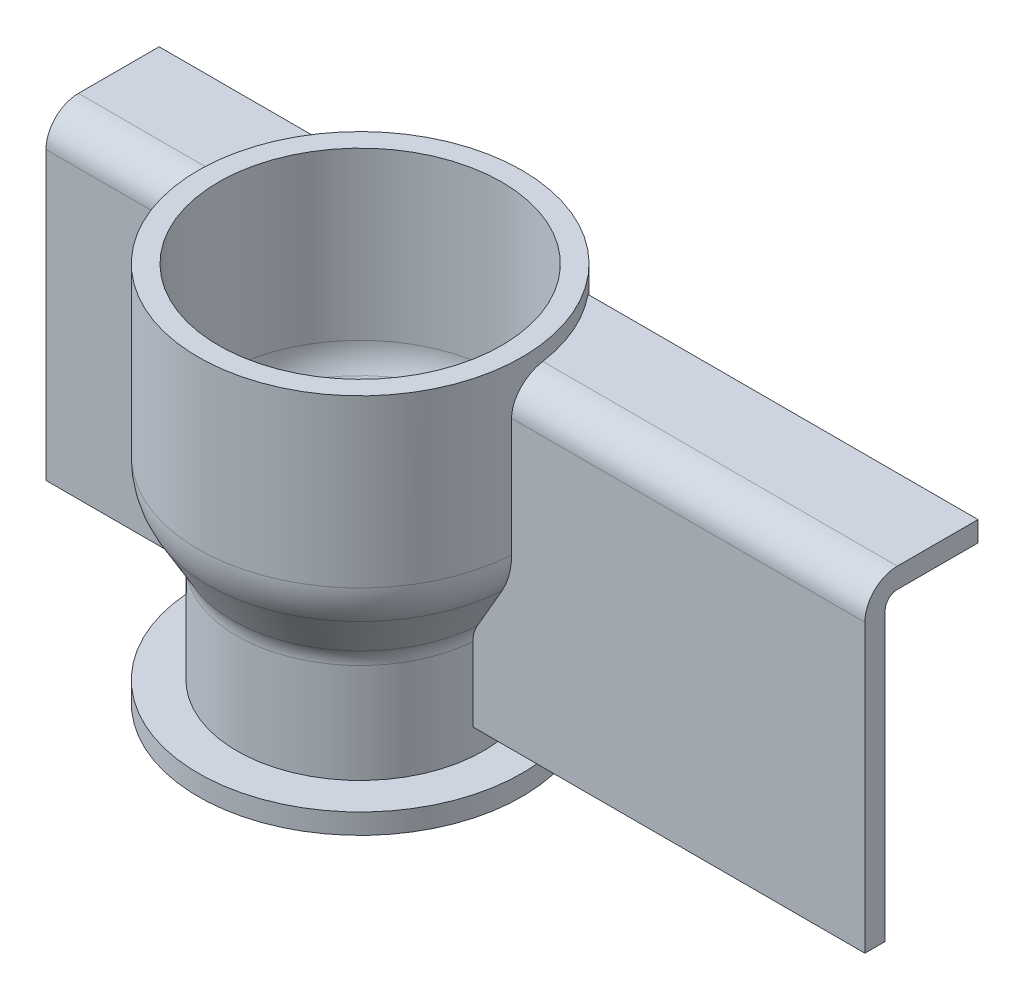
SolidWorks part; units mm, degrees
ref_plane "Front Plane" through (0, 0, 0) normal (0, 0, 1) x (1, 0, 0)
ref_plane "Top Plane" through (0, 0, 0) normal (0, 1, 0) x (1, 0, 0)
ref_plane "Right Plane" through (0, 0, 0) normal (1, 0, 0) x (0, 0, -1)
sketch "strainer" plane through (0, 0, 0) normal (0, 0, 1) x (1, 0, 0)
  line L0 (0, 0) -> (0, 47.8971) construction
  line L2 (-34.925, 0) -> (-34.925, -41.047)
  line L3 (-33.2235, -47.397) -> (-27.1015, -58.0007)
  line L4 (-25.4, -64.3507) -> (-25.4, -88.9)
  arc A0 (-25.4, -64.3507) -> (-27.1015, -58.0007) centre (-38.1, -64.3507) ccw
  arc A1 (-33.2235, -47.397) -> (-34.925, -41.047) centre (-22.225, -41.047) cw
  point P9 (-25.4, -60.9478)
  dimension "D6" = 12.7
  dimension "D1" = 69.85
  dimension "D2" = 27.9522
  dimension "D3" = 88.9
  dimension "D4" = 50.8
  dimension "D5" = 30
ref_plane "bracket.start" through (127, 0, 0) normal (1, 0, 0) x (0, 0, -1)
sketch "bracket" plane through (127, 0, 0) normal (1, 0, 0) x (0, 0, -1)
  line L0 (0, -6.35) -> (0, -82.55)
  line L1 (0, -6.35) -> (25.4, -6.35)
  dimension "D1" = 6.35
  dimension "D2" = 25.4
  dimension "D3" = 76.2
revolve "旋轉-薄件1" add sketch "strainer" angle 360 about L0
extrude "伸長-薄件1" add sketch "bracket" against normal up to next thin thin type mid plane wall 5
sketch "草圖3" plane through (0, -88.9, 0) normal (0, -1, 0) x (1, 0, 0)
  circle A0 centre (0, 0) radius 39.925 construction
  circle A1 centre (0, 0) radius 39.925
extrude "填料-伸長1" add sketch "草圖3" along normal blind 5
ref_plane "平面1" through (-75, 0, 0) normal (1, 0, 0) x (0, 0, -1)
sketch "草圖4" plane through (-75, 0, 0) normal (1, 0, 0) x (0, 0, -1)
  line L6 (5.5, -8.85) -> (25.4, -8.85)
  line L7 (25.4, -8.85) -> (25.4, -3.85)
  line L8 (25.4, -3.85) -> (5.5, -3.85)
  line L9 (-2.5, -11.85) -> (-2.5, -82.55)
  line L10 (-2.5, -82.55) -> (2.5, -82.55)
  line L11 (2.5, -82.55) -> (2.5, -11.85)
  line L12 (5.5, -8.85) -> (25.4, -8.85)
  line L13 (25.4, -8.85) -> (25.4, -3.85)
  line L14 (25.4, -3.85) -> (5.5, -3.85)
  line L15 (-2.5, -11.85) -> (-2.5, -82.55)
  line L16 (-2.5, -82.55) -> (2.5, -82.55)
  line L17 (2.5, -82.55) -> (2.5, -11.85)
  arc A2 (5.5, -3.85) -> (-2.5, -11.85) centre (5.5, -11.85) ccw
  arc A3 (5.5, -8.85) -> (2.5, -11.85) centre (5.5, -11.85) ccw
  arc A4 (5.5, -3.85) -> (-2.5, -11.85) centre (5.5, -11.85) ccw
  arc A5 (5.5, -8.85) -> (2.5, -11.85) centre (5.5, -11.85) ccw
  dimension "D1" = 0
extrude "填料-伸長3" add sketch "草圖4" along normal up to next
